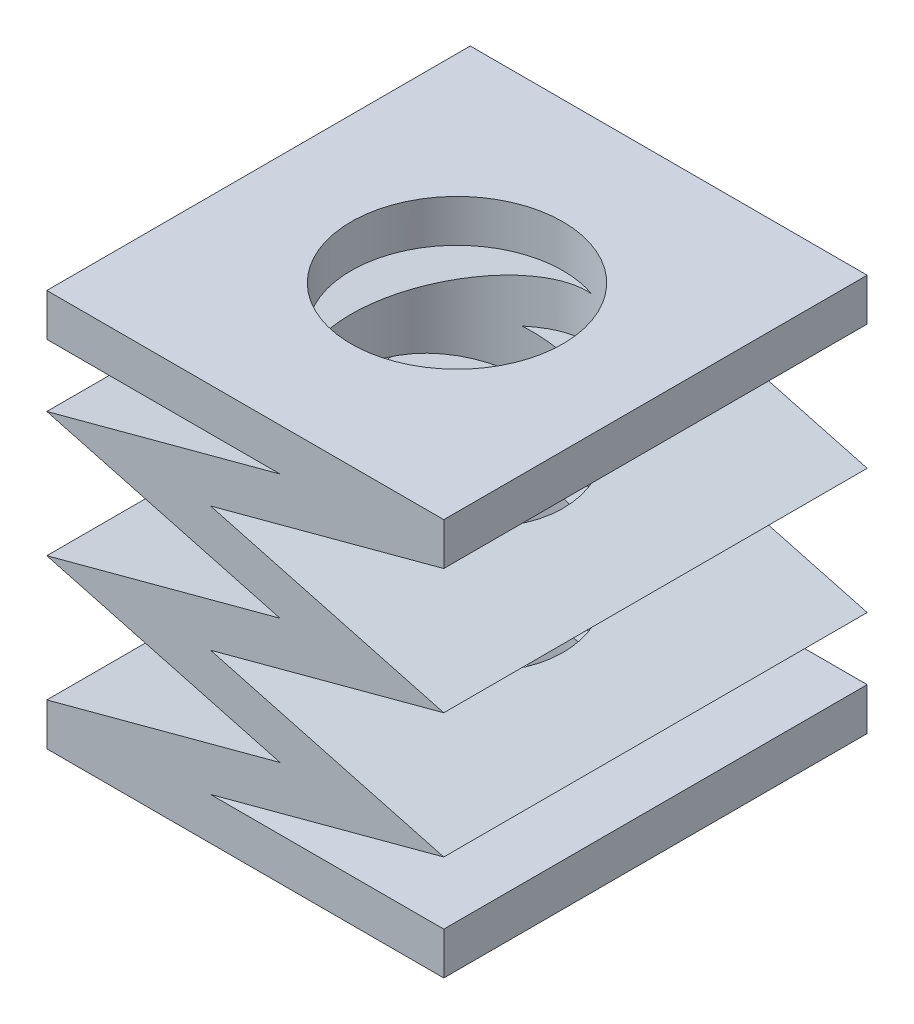
SolidWorks part; units mm, degrees
material "ABS"
ref_plane "Front Plane" through (0, 0, 0) normal (0, 0, 1) x (1, 0, 0)
ref_plane "Top Plane" through (0, 0, 0) normal (0, 1, 0) x (1, 0, 0)
ref_plane "Right Plane" through (0, 0, 0) normal (1, 0, 0) x (0, 0, -1)
sketch "Sketch1" plane through (0, 0, 0) normal (0, 0, 1) x (1, 0, 0)
  line L0 (7.5, 2.6667) -> (2.2186, 0)
  line L1 (7.5, 2.6667) -> (5.2814, 2.6667) construction
  line L2 (5.2814, 2.6667) -> (0, 0)
  line L3 (0, 0) -> (2.2186, 0)
  line L4 (2.6407, 1.3333) -> (3.0914, 0.4407) construction
  line L5 (0, 5.3333) -> (2.2186, 5.3333) construction
  line L6 (7.5, 2.6667) -> (2.2186, 5.3333)
  line L7 (5.2814, 2.6667) -> (0, 5.3333)
  line L8 (7.5, 8) -> (2.2186, 5.3333)
  line L9 (5.2814, 8) -> (0, 5.3333)
  line L10 (7.5, 8) -> (5.2814, 8) construction
  line L11 (7.5, 8) -> (5.2814, 8)
  line L12 (7.5, 0) -> (7.5, 2.6667) construction
  line L13 (0, 0) -> (7.5, 0)
  line L14 (0, 0) -> (0, -1)
  line L15 (0, -1) -> (7.5, -1)
  line L16 (7.5, 0) -> (7.5, -1)
  line L17 (7.5, 8) -> (7.5, 0) construction
  line L18 (0, 8) -> (0, 9)
  line L19 (7.5, 4) -> (0, 4) construction
  line L20 (0, 4) -> (0, 0) construction
  line L21 (0, 9) -> (7.5, 9)
  line L22 (7.5, 8) -> (7.5, 9)
  line L23 (0, 8) -> (7.5, 8)
  dimension "D1" = 1
  dimension "D2" = 7.5
  dimension "D3" = 10
  dimension "D4" = 1
extrude "Boss-Extrude1" [suppressed] add sketch "Sketch1" along normal blind 10 contours L16 L13 L3 L14 L15 | L8 L11 L9 L7 L2 L3 L0 L6 | L18 L23 L11 L22 L21
sketch "Sketch2" [suppressed] plane through (0, -1, 0) normal (0, -1, 0) x (1, 0, 0)
  line L0 (3.75, 10) -> (3.75, 0) construction
  line L1 (0, 10) -> (7.5, 10) construction
  line L2 (0, 0) -> (7.5, 0) construction
  circle A0 centre (3.75, 5) radius 2
  dimension "D1" = 4
extrude "Cut-Extrude1" [suppressed] cut sketch "Sketch2" against normal through all
sketch "Sketch3" plane through (0, 0, 0) normal (0, 0, 1) x (1, 0, 0)
  line L0 (7.5, 1.18) -> (3.093, 0)
  line L1 (7.5, 1.18) -> (4.407, 1.18) construction
  line L2 (4.407, 1.18) -> (0, 0)
  line L3 (0, 0) -> (3.093, 0)
  line L5 (0, 2.36) -> (3.093, 2.36) construction
  line L6 (7.5, 1.18) -> (3.093, 2.36)
  line L7 (4.407, 1.18) -> (0, 2.36)
  line L8 (7.5, 3.54) -> (3.093, 2.36)
  line L9 (4.407, 3.54) -> (0, 2.36)
  line L10 (7.5, 3.54) -> (4.407, 3.54) construction
  line L11 (7.5, 3.54) -> (4.407, 3.54) construction
  line L12 (7.5, 0) -> (7.5, 1.18) construction
  line L13 (0, 0) -> (7.5, 0)
  line L14 (0, 0) -> (0, -0.8)
  line L15 (0, -0.8) -> (7.5, -0.8)
  line L16 (7.5, 0) -> (7.5, -0.8)
  line L17 (7.5, 3.54) -> (7.5, 0) construction
  line L18 (4.407, 3.54) -> (0, 4.72)
  line L19 (7.5, 1.77) -> (0, 1.77) construction
  line L20 (0, 1.77) -> (0, 0) construction
  line L21 (7.5, 3.54) -> (3.093, 4.72)
  line L22 (7.5, 5.9) -> (3.093, 4.72)
  line L23 (4.407, 5.9) -> (0, 4.72)
  line L24 (4.407, 5.9) -> (7.5, 5.9)
  line L25 (7.5, 5.9) -> (7.5, 0) construction
  line L26 (7.5, 2.95) -> (0, 2.95) construction
  line L27 (0, 2.95) -> (0, 1.77) construction
  line L28 (7.5, 5.9) -> (7.5, 6.7)
  line L29 (0, 5.9) -> (7.5, 5.9)
  line L30 (0, 5.9) -> (0, 6.7)
  line L31 (0, 6.7) -> (7.5, 6.7)
  dimension "D1" = 0.8
  dimension "D2" = 7.5
  dimension "D3" = 7.5
  dimension "D4" = 0.8
extrude "Boss-Extrude3" add sketch "Sketch3" along normal blind 8 contours L16 L13 L3 L14 L15 | L24 L23 L18 L9 L7 L2 L3 L0 L6 L8 L21 L22 | L31 L30 L29 L24 L28
sketch "Sketch4" plane through (0, -0.8, 0) normal (0, -1, 0) x (1, 0, 0)
  line L0 (3.75, 8) -> (3.75, 0) construction
  line L1 (0, 8) -> (7.5, 8) construction
  line L2 (0, 0) -> (7.5, 0) construction
  circle A0 centre (3.75, 4) radius 2
  dimension "D1" = 4
extrude "Cut-Extrude3" cut sketch "Sketch4" against normal through all
